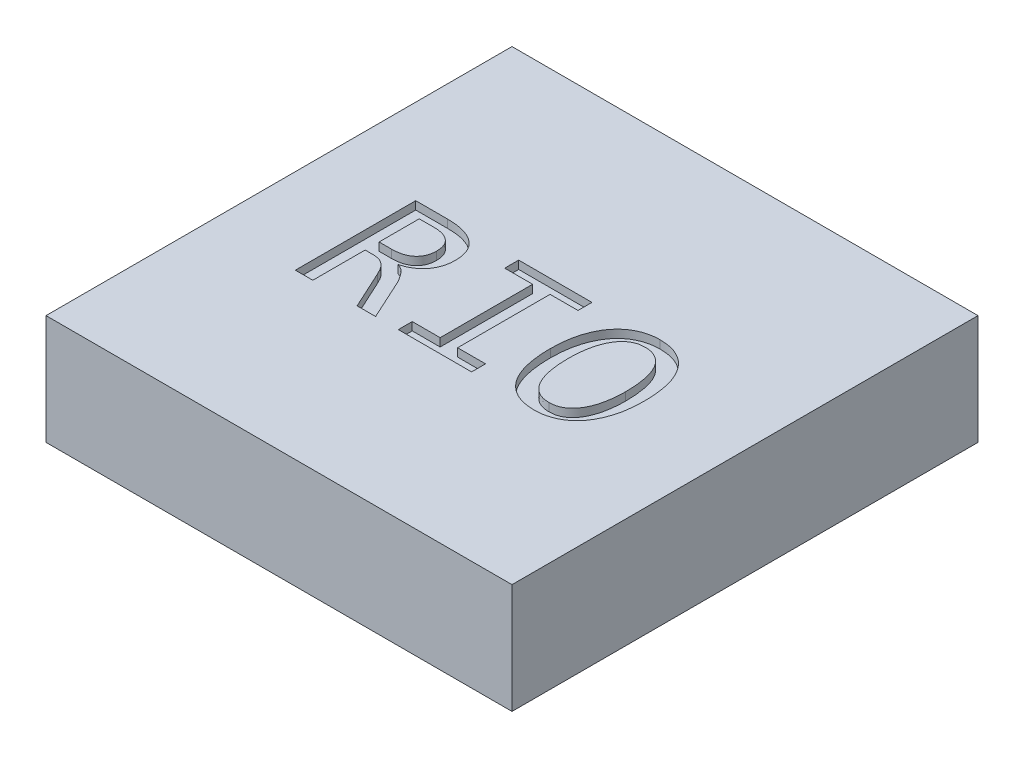
SolidWorks part; units mm, degrees
ref_plane "Front Plane" through (0, 0, 0) normal (0, 0, 1) x (1, 0, 0)
ref_plane "Top Plane" through (0, 0, 0) normal (0, 1, 0) x (1, 0, 0)
ref_plane "Right Plane" through (0, 0, 0) normal (1, 0, 0) x (0, 0, -1)
sketch "Sketch1" plane through (0, 0, 0) normal (0, 1, 0) x (1, 0, 0)
  line L1 (0, 0) -> (146.05, 0)
  line L2 (0, 0) -> (0, 146.05)
  line L3 (0, 146.05) -> (146.05, 146.05)
  line L4 (146.05, 0) -> (146.05, 146.05)
  dimension "D1" = 146.05
extrude "Boss-Extrude1" add sketch "Sketch1" along normal mid plane 34.417
sketch "Sketch2" plane through (0, 17.2085, 0) normal (0, 1, 0) x (1, 0, 0)
  text T0 "RIO" font "Consolas" height in points 144
extrude "Cut-Extrude1" cut sketch "Sketch2" against normal blind 2.54
